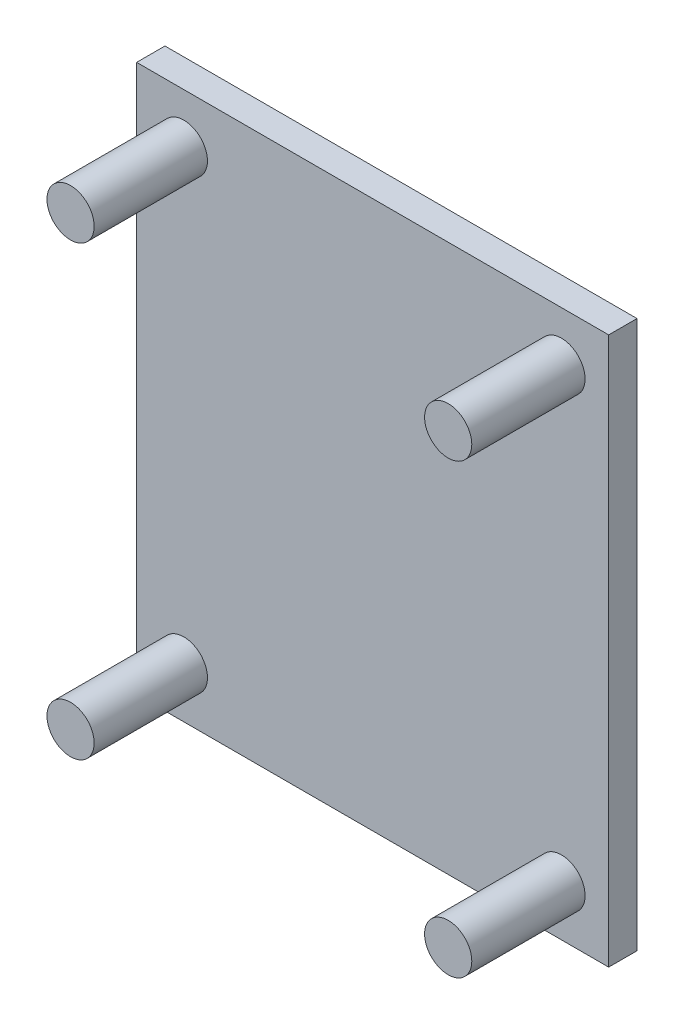
SolidWorks part; units mm, degrees
ref_plane "Спереди" through (0, 0, 0) normal (0, 0, 1) x (1, 0, 0)
ref_plane "Сверху" through (0, 0, 0) normal (0, 1, 0) x (1, 0, 0)
ref_plane "Справа" through (0, 0, 0) normal (1, 0, 0) x (0, 0, -1)
sketch "Эскиз1" plane through (0, 0, 0) normal (0, 0, 1) x (1, 0, 0)
  line L0 (-25, -29) -> (25, -29)
  line L1 (25, -29) -> (25, 29)
  line L2 (25, 29) -> (-25, 29)
  line L3 (-25, 29) -> (-25, -29)
extrude "Former_base" add sketch "Эскиз1" along normal blind 3
sketch "Эскиз2" plane through (0, 0, 0) normal (0, 0, 1) x (1, 0, 0)
  circle A0 centre (-20, -23.7) radius 2.5
  circle A1 centre (-20, 23.7) radius 2.5
  circle A2 centre (20, -23.7) radius 2.5
  circle A3 centre (20, 23.7) radius 2.5
extrude "Former_posts" add sketch "Эскиз2" along normal blind 12 from offset 3
